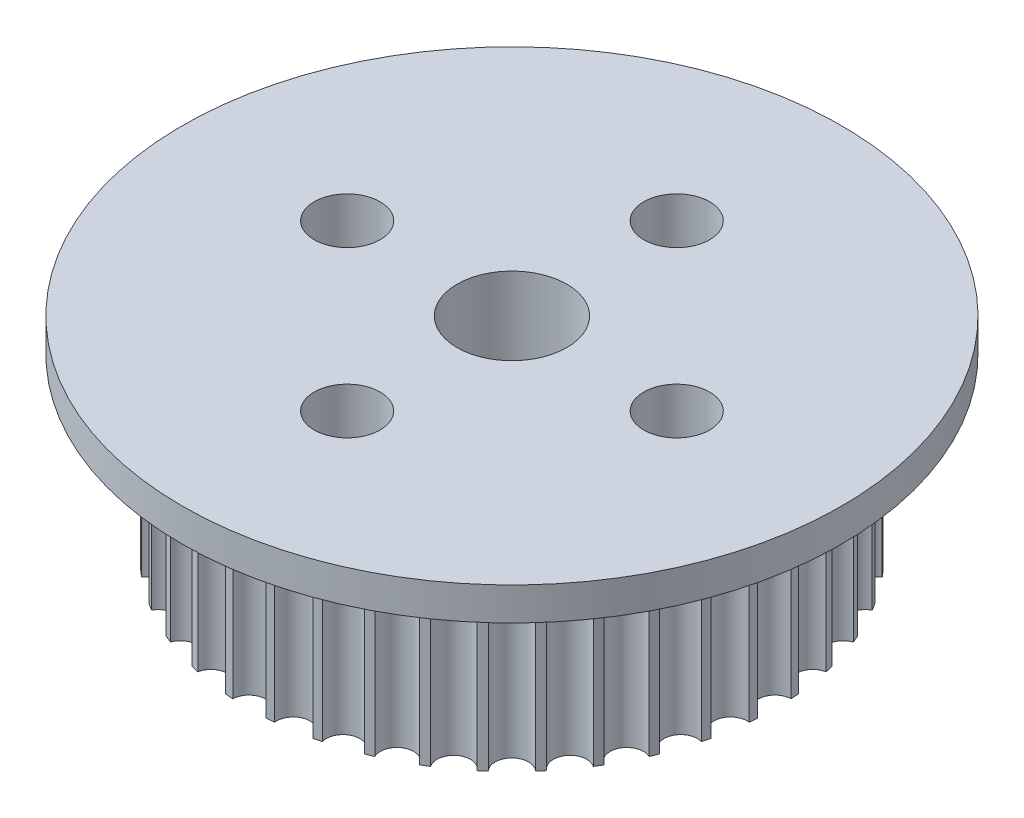
SolidWorks part; units mm, degrees
material "ABS"
ref_plane "Front Plane" through (0, 0, 0) normal (0, 0, 1) x (1, 0, 0)
ref_plane "Top Plane" through (0, 0, 0) normal (0, 1, 0) x (1, 0, 0)
ref_plane "Right Plane" through (0, 0, 0) normal (1, 0, 0) x (0, 0, -1)
sketch "Sketch1" plane through (0, 0, 0) normal (0, 1, 0) x (1, 0, 0)
  arc A0 (-2.619, 11.68) -> (-2.969, 11.5959) centre (0, 0) ccw
  arc A1 (-0.7596, 11.9459) -> (0.7596, 11.9459) centre (0, 11.97) ccw
  arc A2 (1.1185, 11.9176) -> (2.619, 11.68) centre (1.8725, 11.8226) ccw
  arc A3 (2.969, 11.5959) -> (4.4139, 11.1265) centre (3.6989, 11.3841) ccw
  arc A4 (4.7465, 10.9887) -> (6.1001, 10.299) centre (5.4343, 10.6653) ccw
  arc A5 (6.4071, 10.1109) -> (7.6362, 9.2179) centre (7.0358, 9.6839) ccw
  arc A6 (7.9099, 8.9841) -> (8.9841, 7.9099) centre (8.4641, 8.4641) ccw
  arc A7 (9.2179, 7.6362) -> (10.1109, 6.4071) centre (9.6839, 7.0358) ccw
  arc A8 (10.299, 6.1001) -> (10.9887, 4.7465) centre (10.6653, 5.4343) ccw
  arc A9 (11.1265, 4.4139) -> (11.5959, 2.969) centre (11.3841, 3.6989) ccw
  arc A10 (11.68, 2.619) -> (11.9176, 1.1185) centre (11.8226, 1.8725) ccw
  arc A11 (11.9459, 0.7596) -> (11.9459, -0.7596) centre (11.97, 0) ccw
  arc A12 (11.9176, -1.1185) -> (11.68, -2.619) centre (11.8226, -1.8725) ccw
  arc A13 (11.5959, -2.969) -> (11.1265, -4.4139) centre (11.3841, -3.6989) ccw
  arc A14 (10.9887, -4.7465) -> (10.299, -6.1001) centre (10.6653, -5.4343) ccw
  arc A15 (10.1109, -6.4071) -> (9.2179, -7.6362) centre (9.6839, -7.0358) ccw
  arc A16 (8.9841, -7.9099) -> (7.9099, -8.9841) centre (8.4641, -8.4641) ccw
  arc A17 (7.6362, -9.2179) -> (6.4071, -10.1109) centre (7.0358, -9.6839) ccw
  arc A18 (6.1001, -10.299) -> (4.7465, -10.9887) centre (5.4343, -10.6653) ccw
  arc A19 (4.4139, -11.1265) -> (2.969, -11.5959) centre (3.6989, -11.3841) ccw
  arc A20 (2.619, -11.68) -> (1.1185, -11.9176) centre (1.8725, -11.8226) ccw
  arc A21 (0.7596, -11.9459) -> (-0.7596, -11.9459) centre (0, -11.97) ccw
  arc A22 (-1.1185, -11.9176) -> (-2.619, -11.68) centre (-1.8725, -11.8226) ccw
  arc A23 (-2.969, -11.5959) -> (-4.4139, -11.1265) centre (-3.6989, -11.3841) ccw
  arc A24 (-4.7465, -10.9887) -> (-6.1001, -10.299) centre (-5.4343, -10.6653) ccw
  arc A25 (-6.4071, -10.1109) -> (-7.6362, -9.2179) centre (-7.0358, -9.6839) ccw
  arc A26 (-7.9099, -8.9841) -> (-8.9841, -7.9099) centre (-8.4641, -8.4641) ccw
  arc A27 (-9.2179, -7.6362) -> (-10.1109, -6.4071) centre (-9.6839, -7.0358) ccw
  arc A28 (-10.299, -6.1001) -> (-10.9887, -4.7465) centre (-10.6653, -5.4343) ccw
  arc A29 (-11.1265, -4.4139) -> (-11.5959, -2.969) centre (-11.3841, -3.6989) ccw
  arc A30 (-11.68, -2.619) -> (-11.9176, -1.1185) centre (-11.8226, -1.8725) ccw
  arc A31 (-11.9459, -0.7596) -> (-11.9459, 0.7596) centre (-11.97, 0) ccw
  arc A32 (-11.9176, 1.1185) -> (-11.68, 2.619) centre (-11.8226, 1.8725) ccw
  arc A33 (-11.5959, 2.969) -> (-11.1265, 4.4139) centre (-11.3841, 3.6989) ccw
  arc A34 (-10.9887, 4.7465) -> (-10.299, 6.1001) centre (-10.6653, 5.4343) ccw
  arc A35 (-10.1109, 6.4071) -> (-9.2179, 7.6362) centre (-9.6839, 7.0358) ccw
  arc A36 (-8.9841, 7.9099) -> (-7.9099, 8.9841) centre (-8.4641, 8.4641) ccw
  arc A37 (-7.6362, 9.2179) -> (-6.4071, 10.1109) centre (-7.0358, 9.6839) ccw
  arc A38 (-6.1001, 10.299) -> (-4.7465, 10.9887) centre (-5.4343, 10.6653) ccw
  arc A39 (-4.4139, 11.1265) -> (-2.969, 11.5959) centre (-3.6989, 11.3841) ccw
  arc A40 (-2.619, 11.68) -> (-1.1185, 11.9176) centre (-1.8725, 11.8226) ccw
  arc A41 (-0.7596, 11.9459) -> (-1.1185, 11.9176) centre (0, 0) ccw
  arc A42 (1.1185, 11.9176) -> (0.7596, 11.9459) centre (0, 0) ccw
  arc A43 (2.969, 11.5959) -> (2.619, 11.68) centre (0, 0) ccw
  arc A44 (4.7465, 10.9887) -> (4.4139, 11.1265) centre (0, 0) ccw
  arc A45 (6.4071, 10.1109) -> (6.1001, 10.299) centre (0, 0) ccw
  arc A46 (7.9099, 8.9841) -> (7.6362, 9.2179) centre (0, 0) ccw
  arc A47 (9.2179, 7.6362) -> (8.9841, 7.9099) centre (0, 0) ccw
  arc A48 (10.299, 6.1001) -> (10.1109, 6.4071) centre (0, 0) ccw
  arc A49 (11.1265, 4.4139) -> (10.9887, 4.7465) centre (0, 0) ccw
  arc A50 (11.68, 2.619) -> (11.5959, 2.969) centre (0, 0) ccw
  arc A51 (11.9459, 0.7596) -> (11.9176, 1.1185) centre (0, 0) ccw
  arc A52 (11.9176, -1.1185) -> (11.9459, -0.7596) centre (0, 0) ccw
  arc A53 (11.5959, -2.969) -> (11.68, -2.619) centre (0, 0) ccw
  arc A54 (10.9887, -4.7465) -> (11.1265, -4.4139) centre (0, 0) ccw
  arc A55 (10.1109, -6.4071) -> (10.299, -6.1001) centre (0, 0) ccw
  arc A56 (8.9841, -7.9099) -> (9.2179, -7.6362) centre (0, 0) ccw
  arc A57 (7.6362, -9.2179) -> (7.9099, -8.9841) centre (0, 0) ccw
  arc A58 (6.1001, -10.299) -> (6.4071, -10.1109) centre (0, 0) ccw
  arc A59 (4.4139, -11.1265) -> (4.7465, -10.9887) centre (0, 0) ccw
  arc A60 (2.619, -11.68) -> (2.969, -11.5959) centre (0, 0) ccw
  arc A61 (0.7596, -11.9459) -> (1.1185, -11.9176) centre (0, 0) ccw
  arc A62 (-1.1185, -11.9176) -> (-0.7596, -11.9459) centre (0, 0) ccw
  arc A63 (-2.969, -11.5959) -> (-2.619, -11.68) centre (0, 0) ccw
  arc A64 (-4.7465, -10.9887) -> (-4.4139, -11.1265) centre (0, 0) ccw
  arc A65 (-6.4071, -10.1109) -> (-6.1001, -10.299) centre (0, 0) ccw
  arc A66 (-7.9099, -8.9841) -> (-7.6362, -9.2179) centre (0, 0) ccw
  arc A67 (-9.2179, -7.6362) -> (-8.9841, -7.9099) centre (0, 0) ccw
  arc A68 (-10.299, -6.1001) -> (-10.1109, -6.4071) centre (0, 0) ccw
  arc A69 (-11.1265, -4.4139) -> (-10.9887, -4.7465) centre (0, 0) ccw
  arc A70 (-11.68, -2.619) -> (-11.5959, -2.969) centre (0, 0) ccw
  arc A71 (-11.9459, -0.7596) -> (-11.9176, -1.1185) centre (0, 0) ccw
  arc A72 (-11.9176, 1.1185) -> (-11.9459, 0.7596) centre (0, 0) ccw
  arc A73 (-11.5959, 2.969) -> (-11.68, 2.619) centre (0, 0) ccw
  arc A74 (-10.9887, 4.7465) -> (-11.1265, 4.4139) centre (0, 0) ccw
  arc A75 (-10.1109, 6.4071) -> (-10.299, 6.1001) centre (0, 0) ccw
  arc A76 (-8.9841, 7.9099) -> (-9.2179, 7.6362) centre (0, 0) ccw
  arc A77 (-7.6362, 9.2179) -> (-7.9099, 8.9841) centre (0, 0) ccw
  arc A78 (-6.1001, 10.299) -> (-6.4071, 10.1109) centre (0, 0) ccw
  arc A79 (-4.4139, 11.1265) -> (-4.7465, 10.9887) centre (0, 0) ccw
  point P86 (0, 0)
  dimension "D1" = 23.94
  dimension "D2" = 1.52
  dimension "D3" = 40
extrude "Boss-Extrude1" add sketch "Sketch1" along normal blind 8
sketch "Sketch2" plane through (0, 8, 0) normal (0, 1, 0) x (1, 0, 0)
  circle A0 centre (0, 0) radius 15
  dimension "D1" = 30
extrude "Boss-Extrude2" add sketch "Sketch2" along normal blind 1.5
sketch "Sketch4" plane through (0, 0, 0) normal (0, -1, 0) x (1, 0, 0)
  line L0 (0, 0) -> (0, 7.5) construction
  circle A0 centre (0, 0) radius 2.5
  point P3 (6.1877, -4.5725)
  point P4 (-5.631, -4.954)
  point P5 (-5.8927, -5.1842)
  point P6 (0, 7.7547)
  point P8 (5.9449, -4.5725)
  point P9 (0, 7.5)
  dimension "D1" = 5
  dimension "D8" = 7.5
extrude "Cut-Extrude1" cut sketch "Sketch4" against normal blind 23
sketch "Sketch5" plane through (0, 0, 0) normal (0, -1, 0) x (1, 0, 0)
  circle A0 centre (0, 7.5) radius 1.5
  circle A1 centre (7.5, 0) radius 1.5
  circle A2 centre (0, -7.5) radius 1.5
  circle A3 centre (-7.5, 0) radius 1.5
  point P2 (-7.4906, 0)
  point P4 (-7.6233, 0)
  dimension "D1" = 3
  dimension "D2" = 7.5
  dimension "D4" = 7.5
  dimension "D3" = 4
extrude "Cut-Extrude2" cut sketch "Sketch5" against normal through all
